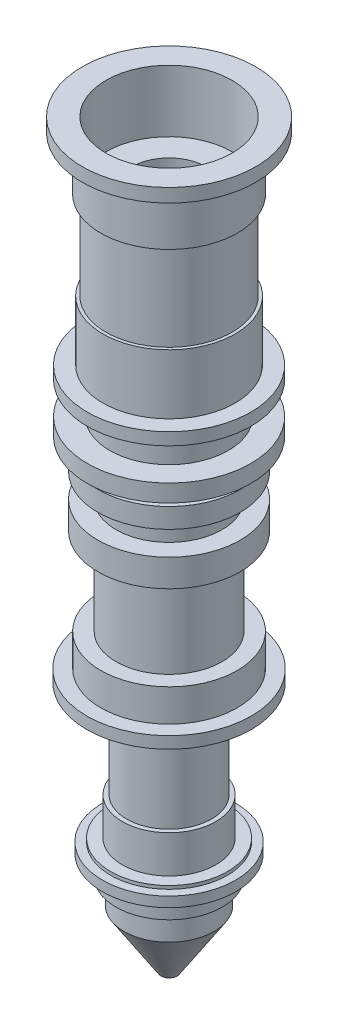
SolidWorks part; units mm, degrees
ref_plane "前视基准面" through (0, 0, 0) normal (0, 0, 1) x (1, 0, 0)
ref_plane "上视基准面" through (0, 0, 0) normal (0, 1, 0) x (1, 0, 0)
ref_plane "右视基准面" through (0, 0, 0) normal (1, 0, 0) x (0, 0, -1)
sketch "草图1" plane through (0, 0, 0) normal (0, 0, 1) x (1, 0, 0)
  line L0 (0, 0) -> (0, 690.98) construction
  line L1 (0, 0) -> (7.5, 0)
  line L2 (7.5, 0) -> (42.09, 53.35)
  line L3 (42.09, 53.35) -> (42.09, 76.73)
  line L4 (42.09, 76.73) -> (49.525, 76.73)
  line L5 (49.525, 76.73) -> (49.525, 95.5)
  line L6 (49.525, 95.5) -> (62.215, 95.5)
  line L7 (62.215, 95.5) -> (62.215, 104.91)
  line L8 (62.215, 104.91) -> (54.51, 104.91)
  line L9 (54.51, 104.91) -> (54.51, 107.98)
  line L10 (54.51, 107.98) -> (43.65, 107.98)
  line L11 (43.65, 107.98) -> (43.65, 142.98)
  line L12 (43.65, 142.98) -> (39.635, 142.98)
  line L13 (39.635, 142.98) -> (39.635, 246.28)
  line L14 (39.635, 246.28) -> (42.62, 246.28)
  line L15 (42.62, 246.28) -> (42.62, 233.91)
  line L16 (42.62, 233.91) -> (76.8, 233.91)
  line L17 (76.8, 233.91) -> (76.8, 244.9)
  line L18 (76.8, 244.9) -> (63.67, 244.9)
  line L19 (63.67, 244.9) -> (63.67, 275.1)
  line L20 (63.67, 275.1) -> (49.47, 275.1)
  line L21 (49.47, 275.1) -> (49.47, 356.23)
  line L22 (49.47, 356.23) -> (66.395, 356.23)
  line L23 (66.395, 356.23) -> (66.395, 381.8)
  line L24 (66.395, 381.8) -> (49.47, 381.8)
  line L25 (49.47, 381.8) -> (49.47, 404.27)
  line L26 (49.47, 404.27) -> (66.395, 404.27)
  line L27 (66.395, 404.27) -> (66.395, 422.79)
  line L28 (66.395, 422.79) -> (39.72, 422.79)
  line L29 (39.72, 422.79) -> (39.72, 432.61)
  line L30 (39.72, 432.61) -> (76.34, 432.61)
  line L31 (76.34, 432.61) -> (76.34, 448.79)
  line L32 (76.34, 448.79) -> (55.36, 448.79)
  line L33 (55.36, 448.79) -> (55.36, 478.82)
  line L34 (55.36, 478.82) -> (76.34, 478.82)
  line L35 (76.34, 478.82) -> (76.34, 490.29)
  line L36 (76.34, 490.29) -> (61.69, 490.29)
  line L37 (61.69, 490.29) -> (61.69, 546.17)
  line L38 (61.69, 546.17) -> (58.9, 546.17)
  line L39 (58.9, 546.17) -> (58.9, 628.71)
  line L40 (58.9, 628.71) -> (63.765, 628.71)
  line L41 (63.765, 628.71) -> (63.765, 678.34)
  line L42 (63.765, 678.34) -> (80.93, 678.34)
  line L43 (80.93, 678.34) -> (80.93, 690.98)
  line L44 (80.93, 690.98) -> (58.9, 690.98)
  line L45 (58.9, 690.98) -> (58.9, 633.2)
  line L46 (58.9, 633.2) -> (34.64, 633.2)
  line L47 (34.64, 633.2) -> (34.64, 422.88)
  line L48 (34.64, 422.88) -> (0, 422.88)
  line L49 (0, 422.88) -> (0, 0)
  dimension "D1" = 15
  dimension "D2" = 53.35
  dimension "D3" = 84.18
  dimension "D4" = 99.05
  dimension "D5" = 23.38
  dimension "D6" = 18.77
  dimension "D7" = 124.43
  dimension "D8" = 9.41
  dimension "D9" = 109.02
  dimension "D10" = 3.07
  dimension "D11" = 87.3
  dimension "D12" = 35
  dimension "D13" = 79.27
  dimension "D14" = 103.3
  dimension "D15" = 90.93
  dimension "D16" = 85.24
  dimension "D17" = 153.6
  dimension "D18" = 10.99
  dimension "D19" = 127.34
  dimension "D20" = 30.2
  dimension "D21" = 98.94
  dimension "D22" = 81.13
  dimension "D23" = 132.79
  dimension "D24" = 25.57
  dimension "D26" = 132.79
  dimension "D25" = 98.94
  dimension "D27" = 22.47
  dimension "D28" = 18.52
  dimension "D29" = 39.72
  dimension "D30" = 9.82
  dimension "D31" = 152.68
  dimension "D32" = 16.18
  dimension "D33" = 110.72
  dimension "D34" = 30.03
  dimension "D35" = 11.47
  dimension "D36" = 152.68
  dimension "D37" = 123.38
  dimension "D38" = 117.8
  dimension "D39" = 127.53
  dimension "D40" = 161.86
  dimension "D41" = 55.88
  dimension "D42" = 82.54
  dimension "D43" = 49.63
  dimension "D44" = 12.64
  dimension "D45" = 117.8
  dimension "D46" = 57.78
  dimension "D47" = 69.28
  dimension "D48" = 210.32
revolve "旋转1" add sketch "草图1" angle 360 about L0
sketch "草图2" plane through (0, 422.88, 0) normal (0, 1, 0) x (1, 0, 0)
  circle A0 centre (0, 0) radius 4
  dimension "D1" = 8
extrude "凸台-拉伸1" add sketch "草图2" along normal blind 11.36
sketch "草图3" plane through (0, 434.24, 0) normal (0, 1, 0) x (1, 0, 0)
  line L1 (7.3497, 0) -> (3.6748, 6.365)
  line L2 (3.6748, 6.365) -> (-3.6748, 6.365)
  line L3 (-3.6748, 6.365) -> (-7.3497, 0)
  line L4 (-7.3497, 0) -> (-3.6748, -6.365)
  line L5 (-3.6748, -6.365) -> (3.6748, -6.365)
  line L6 (3.6748, -6.365) -> (7.3497, 0)
  circle A0 centre (0, 0) radius 6.365 construction
  dimension "D1" = 12.73
extrude "凸台-拉伸2" add sketch "草图3" along normal blind 102
sketch "草图4" plane through (0, 536.24, 0) normal (0, 1, 0) x (1, 0, 0)
  circle A0 centre (0, 0) radius 3.42
  dimension "D1" = 6.84
extrude "凸台-拉伸3" add sketch "草图4" along normal blind 22
equation "\"D26@草图1\"=\"D23@草图1\""
equation "\"D25@草图1\"=\"D21@草图1\""
